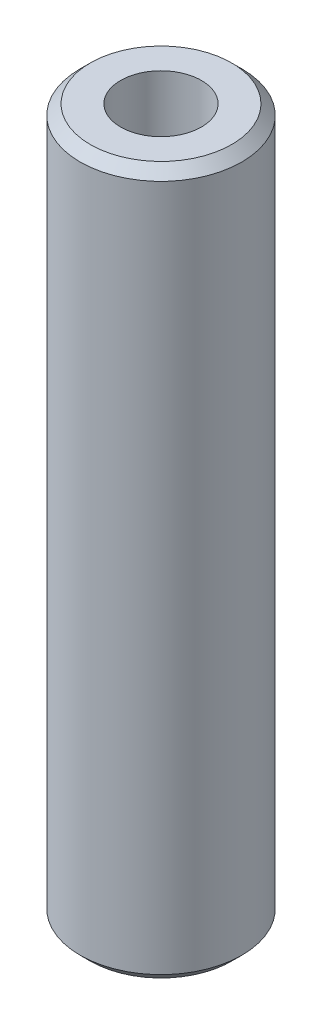
SolidWorks part; units mm, degrees
ref_plane "Front Plane" through (0, 0, 0) normal (0, 0, 1) x (1, 0, 0)
ref_plane "Top Plane" through (0, 0, 0) normal (0, 1, 0) x (1, 0, 0)
ref_plane "Right Plane" through (0, 0, 0) normal (1, 0, 0) x (0, 0, -1)
sketch "Sketch1" plane through (0, 0, 0) normal (0, 1, 0) x (1, 0, 0)
  circle A0 centre (0, 0) radius 2
  circle A1 centre (0, 0) radius 4
  dimension "D1" = 4
  dimension "D2" = 2
extrude "Boss-Extrude1" add sketch "Sketch1" along normal blind 35
chamfer "Chamfer1" distance 0.5 angle 45 2 edges at (0, 0, 4) (0, 35, 4)
